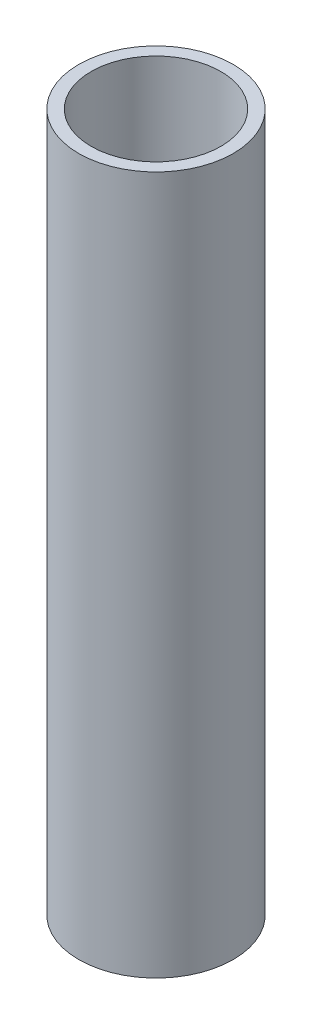
SolidWorks part; units mm, degrees
ref_plane "Front Plane" through (0, 0, 0) normal (0, 0, 1) x (1, 0, 0)
ref_plane "Top Plane" through (0, 0, 0) normal (0, 1, 0) x (1, 0, 0)
ref_plane "Right Plane" through (0, 0, 0) normal (1, 0, 0) x (0, 0, -1)
sketch "Sketch1" plane through (0, 0, 0) normal (0, 1, 0) x (1, 0, 0)
  circle A0 centre (0, 0) radius 12.5
  circle A1 centre (0, 0) radius 10.5
  dimension "D1" = 25
  dimension "D2" = 21
extrude "Boss-Extrude1" add sketch "Sketch1" along normal blind 113
equation "\"cf_tube_outer_diameter\" = 25mm"
equation "\"cf_tube_inner_diameter\" = 21mm"
equation "\"mid_plate_mid_to_top\" = 100mm"
equation "\"mid_plate_mid_to_bottom\" = 125mm"
equation "\"mid_plate_horizontal_spacing\" = 250mm"
equation "\"cf_plate_thickness\" = 4mm"
equation "\"mid_tube_length\" = 500mm"
equation "\"D1@Sketch1\"=\"cf_tube_outer_diameter\""
equation "\"D2@Sketch1\"=\"cf_tube_inner_diameter\""
